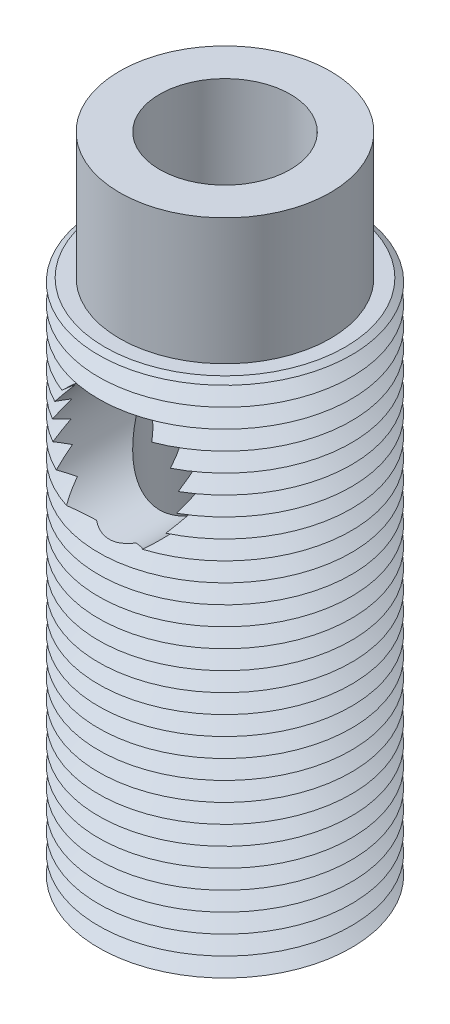
SolidWorks part; units mm, degrees
ref_plane "前视基准面" through (0, 0, 0) normal (0, 0, 1) x (1, 0, 0)
ref_plane "上视基准面" through (0, 0, 0) normal (0, 1, 0) x (1, 0, 0)
ref_plane "右视基准面" through (0, 0, 0) normal (1, 0, 0) x (0, 0, -1)
sketch "草图1" plane through (0, 0, 0) normal (0, 0, 1) x (1, 0, 0)
  line B0 (0, 0) -> (0, 31)
  line B1 (5.25, 0) -> (0, 0)
  line B2 (5.25, 0) -> (6, 0.4513)
  line B3 (5, 31) -> (0, 31)
  line B4 (5, 25) -> (5, 31)
  line B5 (5.7034, 25) -> (5, 25)
  line B6 (5.25, 0.9026) -> (6, 0.4513)
  line B7 (5.25, 0.9026) -> (6, 1.3539)
  line B8 (5.25, 1.8052) -> (6, 1.3539)
  line B9 (5.25, 1.8052) -> (6, 2.2565)
  line B10 (5.25, 2.7078) -> (6, 2.2565)
  line B11 (5.25, 2.7078) -> (6, 3.1591)
  line B12 (5.25, 3.6104) -> (6, 3.1591)
  line B13 (5.25, 3.6104) -> (6, 4.0617)
  line B14 (5.25, 4.513) -> (6, 4.0617)
  line B15 (5.25, 4.513) -> (6, 4.9643)
  line B16 (5.25, 5.4156) -> (6, 4.9643)
  line B17 (5.25, 5.4156) -> (6, 5.8669)
  line B18 (5.25, 6.3182) -> (6, 5.8669)
  line B19 (5.25, 6.3182) -> (6, 6.7695)
  line B20 (5.25, 7.2208) -> (6, 6.7695)
  line B21 (5.25, 7.2208) -> (6, 7.6721)
  line B22 (5.25, 8.1234) -> (6, 7.6721)
  line B23 (5.25, 8.1234) -> (6, 8.5747)
  line B24 (5.25, 9.026) -> (6, 8.5747)
  line B25 (5.25, 9.026) -> (6, 9.4773)
  line B26 (5.25, 9.9286) -> (6, 9.4773)
  line B27 (5.25, 9.9286) -> (6, 10.3799)
  line B28 (5.25, 10.8312) -> (6, 10.3799)
  line B29 (5.25, 10.8312) -> (6, 11.2825)
  line B30 (5.25, 11.7338) -> (6, 11.2825)
  line B31 (5.25, 11.7338) -> (6, 12.1851)
  line B32 (5.25, 12.6364) -> (6, 12.1851)
  line B33 (5.25, 12.6364) -> (6, 13.0877)
  line B34 (5.25, 13.539) -> (6, 13.0877)
  line B35 (5.25, 13.539) -> (6, 13.9903)
  line B36 (5.25, 14.4416) -> (6, 13.9903)
  line B37 (5.25, 14.4416) -> (6, 14.8929)
  line B38 (5.25, 15.3442) -> (6, 14.8929)
  line B39 (5.25, 15.3442) -> (6, 15.7955)
  line B40 (5.25, 16.2468) -> (6, 15.7955)
  line B41 (5.25, 16.2468) -> (6, 16.6981)
  line B42 (5.25, 17.1494) -> (6, 16.6981)
  line B43 (5.25, 17.1494) -> (6, 17.6007)
  line B44 (5.25, 18.052) -> (6, 17.6007)
  line B45 (5.25, 18.052) -> (6, 18.5033)
  line B46 (5.25, 18.9546) -> (6, 18.5033)
  line B47 (5.25, 18.9546) -> (6, 19.4059)
  line B48 (5.25, 19.8572) -> (6, 19.4059)
  line B49 (5.25, 19.8572) -> (6, 20.3085)
  line B50 (5.25, 20.7598) -> (6, 20.3085)
  line B51 (5.25, 20.7598) -> (6, 21.2111)
  line B52 (5.25, 21.6624) -> (6, 21.2111)
  line B53 (5.25, 21.6624) -> (6, 22.1137)
  line B54 (5.25, 22.565) -> (6, 22.1137)
  line B55 (5.25, 22.565) -> (6, 23.0163)
  line B56 (5.25, 23.4676) -> (6, 23.0163)
  line B57 (5.25, 23.4676) -> (6, 23.9189)
  line B58 (5.25, 24.3702) -> (6, 23.9189)
  line B59 (5.25, 24.3702) -> (6, 24.8215)
  line B60 (5.7034, 25) -> (6, 24.8215)
sketch_block_instance "A$C5FB664B2-1"
sketch_block "A$C5FB664B2"
revolve "旋转1" add sketch "草图1" angle 360 about L0
sketch "草图3" plane through (0, 0, 0) normal (0, 0, 1) x (1, 0, 0)
  line L0 (5, 31) -> (-5, 31) construction
  circle A0 centre (0, 20) radius 3
  dimension "D1" = 11
extrude "切除-拉伸1" cut sketch "草图3" against normal through all and the other way through all
sketch "草图4" plane through (0, 31, 0) normal (0, 1, 0) x (1, 0, 0)
  circle A0 centre (0, 0) radius 3.1
extrude "切除-拉伸2" cut sketch "草图4" against normal blind 25
sketch "草图5" plane through (0, 0, 0) normal (0, -1, 0) x (1, 0, 0)
  line L1 (3.5796, 0) -> (1.7898, 3.1)
  line L2 (1.7898, 3.1) -> (-1.7898, 3.1)
  line L3 (-1.7898, 3.1) -> (-3.5796, 0)
  line L4 (-3.5796, 0) -> (-1.7898, -3.1)
  line L5 (-1.7898, -3.1) -> (1.7898, -3.1)
  line L6 (1.7898, -3.1) -> (3.5796, 0)
  circle A0 centre (0, 0) radius 3.1 construction
extrude "切除-拉伸3" cut sketch "草图5" against normal blind 6
